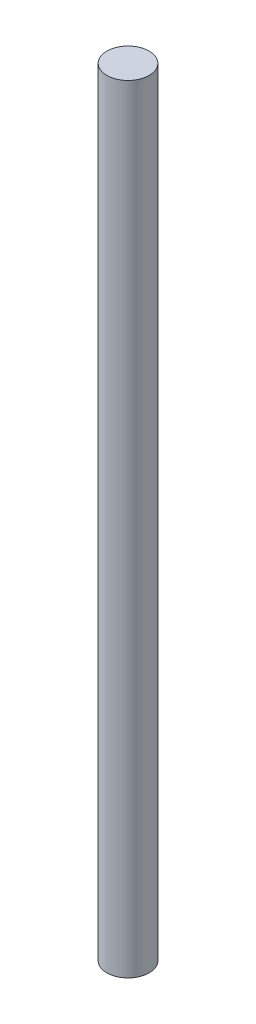
SolidWorks part; units mm, degrees
ref_plane "Front Plane" through (0, 0, 0) normal (0, 0, 1) x (1, 0, 0)
ref_plane "Top Plane" through (0, 0, 0) normal (0, 1, 0) x (1, 0, 0)
ref_plane "Right Plane" through (0, 0, 0) normal (1, 0, 0) x (0, 0, -1)
sketch "Sketch1" plane through (0, 0, 0) normal (0, 1, 0) x (1, 0, 0)
  circle A0 centre (0, 0) radius 12.5
  dimension "D1" = 25
extrude "Boss-Extrude1" add sketch "Sketch1" along normal blind 460
